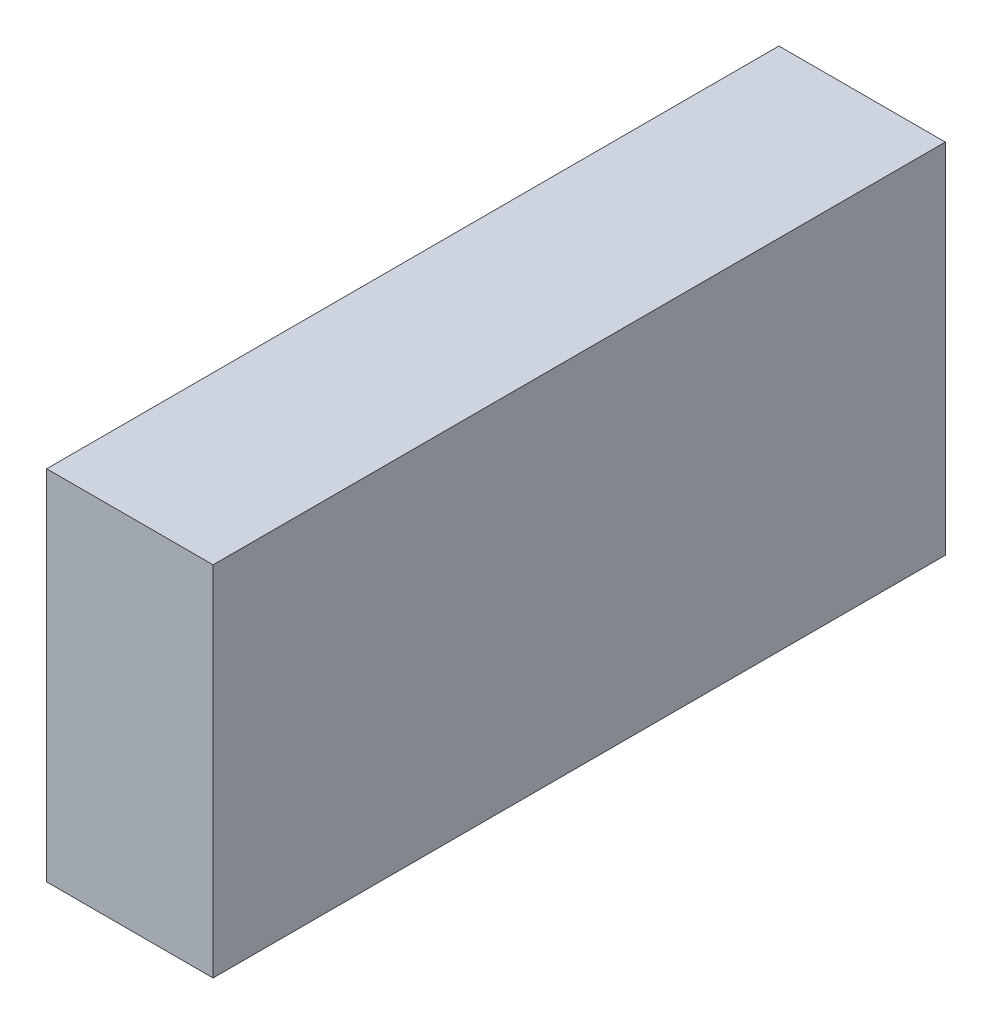
SolidWorks part; units mm, degrees
ref_plane "Front Plane" through (0, 0, 0) normal (0, 0, 1) x (1, 0, 0)
ref_plane "Top Plane" through (0, 0, 0) normal (0, 1, 0) x (1, 0, 0)
ref_plane "Right Plane" through (0, 0, 0) normal (1, 0, 0) x (0, 0, -1)
sketch "Sketch1" plane through (0, 0, 0) normal (0, 1, 0) x (1, 0, 0)
  line L0 (-50, 220) -> (-50, -220)
  line L1 (-50, 220) -> (50, 220)
  line L2 (-50, -220) -> (50, -220)
  line L3 (50, 220) -> (50, -220)
  line L4 (-50, 220) -> (50, -220) construction
  line L5 (-50, -220) -> (50, 220) construction
  point P1 (0, 0)
  dimension "D1" = 440
  dimension "D2" = 100
extrude "Boss-Extrude1" add sketch "Sketch1" along normal blind 215
